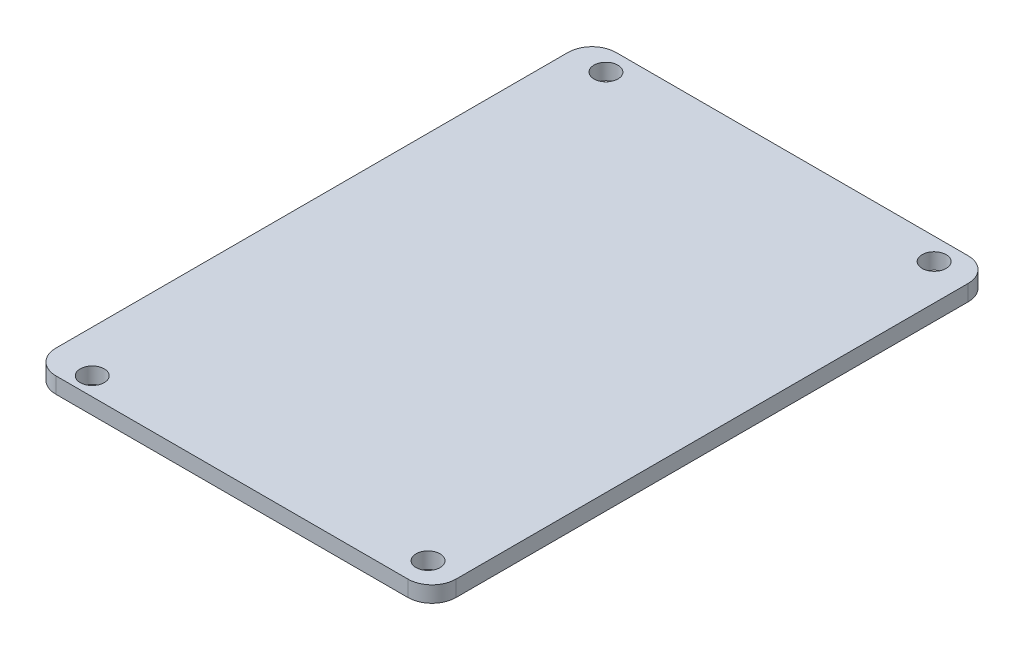
SolidWorks part; units mm, degrees
ref_plane "前视基准面" through (0, 0, 0) normal (0, 0, 1) x (1, 0, 0)
ref_plane "上视基准面" through (0, 0, 0) normal (0, 1, 0) x (1, 0, 0)
ref_plane "右视基准面" through (0, 0, 0) normal (1, 0, 0) x (0, 0, -1)
other "Configuration Table"
sketch "草图1" plane through (0, 0, 0) normal (0, 1, 0) x (1, 0, 0)
  line L0 (0, 48.4697) -> (0, -48.4697) construction
  line L1 (-25, -35) -> (25, -35)
  line L2 (-25, -35) -> (-25, 35)
  line L3 (-25, 35) -> (25, 35)
  line L4 (25, -35) -> (25, 35)
  line L5 (-25, -35) -> (25, 35) construction
  line L6 (-25, 35) -> (25, -35) construction
  line L7 (-41.9563, -0.4952) -> (41.9563, 0.4952) construction
  circle A0 centre (20.5057, 32.2465) radius 1.5
  circle A1 centre (-20.5057, 32.2465) radius 1.5
  circle A2 centre (21.2611, -31.7535) radius 1.5
  circle A3 centre (-19.7389, -32.7215) radius 1.5
  point P0 (0, 0)
  dimension "D3" = 3
  dimension "D5" = 64
  dimension "D1" = 50
  dimension "D2" = 70
  dimension "D4" = 41
extrude "凸台-拉伸1" add sketch "草图1" along normal blind 2
fillet "圆角1" radius 3 4 edges at (-25, 1, -35) (25, 1, -35) (-25, 1, 35) (25, 1, 35)
